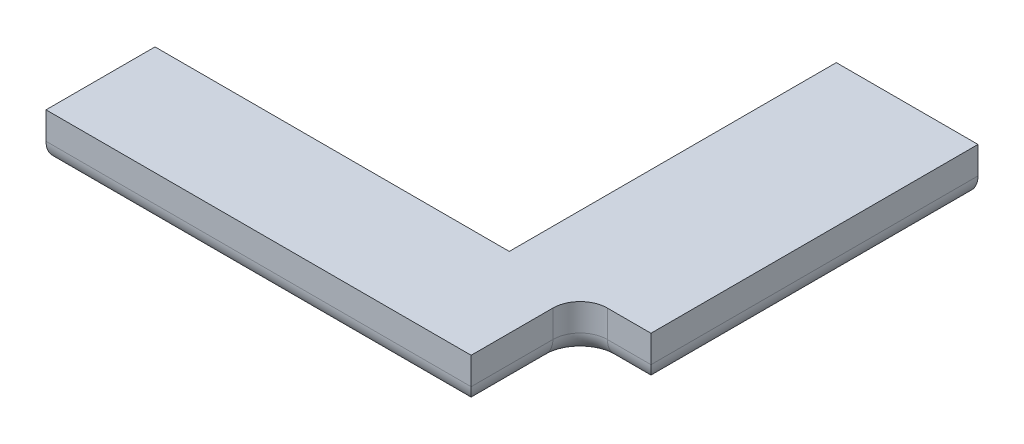
SolidWorks part; units mm, degrees
ref_plane "前基準面" through (0, 0, 0) normal (0, 0, 1) x (1, 0, 0)
ref_plane "上基準面" through (0, 0, 0) normal (0, 1, 0) x (1, 0, 0)
ref_plane "右基準面" through (0, 0, 0) normal (1, 0, 0) x (0, 0, -1)
sketch "草圖1" plane through (0, 0, 0) normal (0, 1, 0) x (1, 0, 0)
  line L0 (0, 0) -> (65, 0)
  line L1 (65, 0) -> (65, 60)
  line L2 (65, 60) -> (91, 60)
  line L3 (91, 60) -> (91, 0)
  line L4 (91, 0) -> (83, 0)
  line L5 (78, -5) -> (78, -20)
  line L6 (78, -20) -> (0, -20)
  line L7 (0, -20) -> (0, 0)
  arc A0 (83, 0) -> (78, -5) centre (83, -5) ccw
  point P9 (83.3613, 0)
  dimension "D6" = 5
  dimension "D1" = 20
  dimension "D2" = 65
  dimension "D3" = 60
  dimension "D4" = 26
  dimension "D5" = 8
extrude "填料-伸長1" add sketch "草圖1" along normal blind 9
fillet "圓角1" radius 4 5 edges at (87, 0, 0) (79.4645, 0, 1.4645) (91, 0, -30) (78, 0, 12.5) (39, 0, 20)
sketch "草圖2" plane through (0, 0, 0) normal (0, -1, 0) x (1, 0, 0)
  line L2 (65, -60) -> (65, 0) construction
  line L3 (87, -60) -> (65, -60) construction
  circle A2 centre (77, -50) radius 6
  circle A3 centre (77, -30) radius 6
  dimension "D6" = 12
  dimension "D7" = 12
  dimension "D8" = 12
  dimension "D9" = 10
  dimension "D10" = 20
extrude "除料-伸長1" cut sketch "草圖2" against normal blind 3
